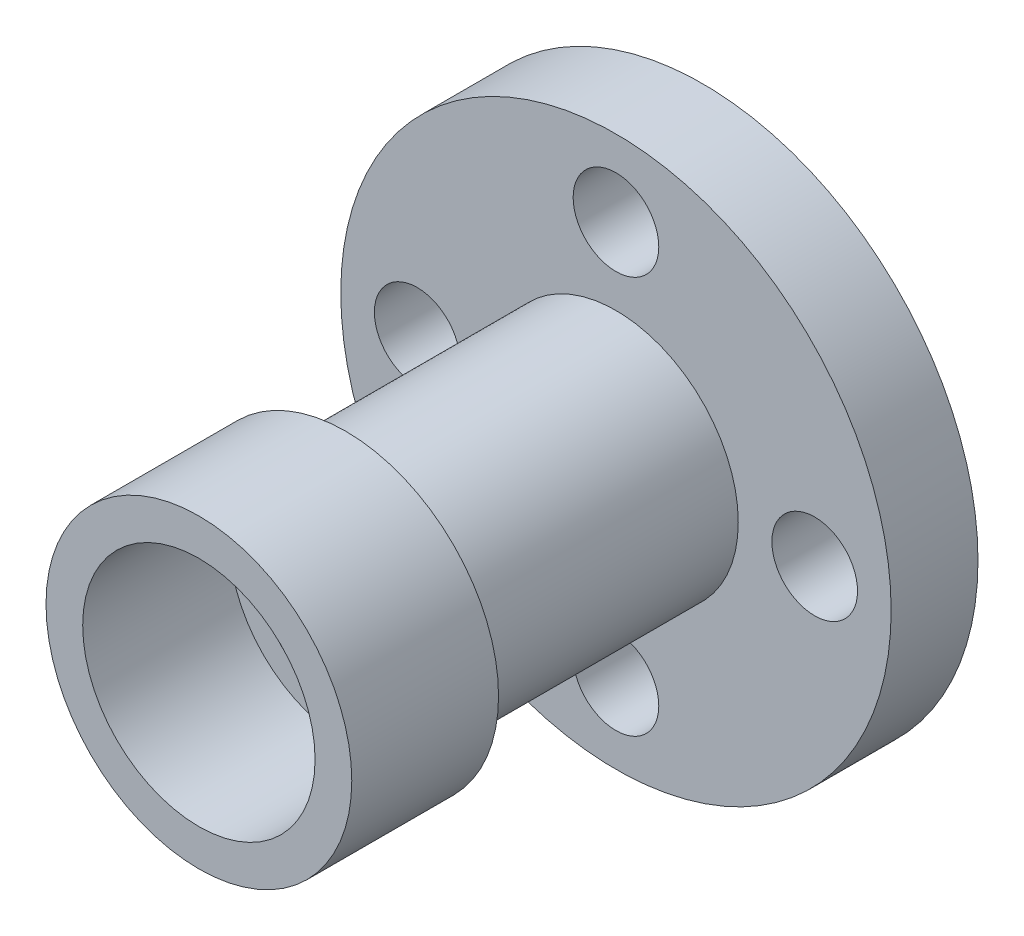
SolidWorks part; units mm, degrees
ref_plane "Alzado" through (0, 0, 0) normal (0, 0, 1) x (1, 0, 0)
ref_plane "Planta" through (0, 0, 0) normal (0, 1, 0) x (1, 0, 0)
ref_plane "Vista lateral" through (0, 0, 0) normal (1, 0, 0) x (0, 0, -1)
sketch "Croquis1" plane through (0, 0, 0) normal (0, 0, 1) x (1, 0, 0)
  circle A1 centre (0, 0) radius 45
extrude "Saliente-Extruir1" add sketch "Croquis1" along normal blind 14.2
sketch "Croquis6" plane through (0, 0, 14.2) normal (0, 0, 1) x (1, 0, 0)
  circle A0 centre (0, 0) radius 15
sketch "Croquis7" plane through (0, 0, 0) normal (0, 0, -1) x (-1, 0, 0)
  line L0 (0, 0) -> (0, 32.5) construction
  circle A0 centre (0, 0) radius 15
  circle A1 centre (0, 32.5) radius 7
  circle A2 centre (32.5, 0) radius 7
  circle A3 centre (0, -32.5) radius 7
  circle A4 centre (-32.5, 0) radius 7
  point P14 (0, 0)
  dimension "D2" = 4
  dimension "D1" = 32.5
sketch "Croquis8" plane through (0, 0, 14.2) normal (0, 0, 1) x (1, 0, 0)
  circle A0 centre (0, 0) radius 15
extrude "Saliente-Extruir13" add sketch "Croquis6" against normal blind 14 contours A0
extrude "Cortar-Extruir3" cut sketch "Croquis8" against normal blind 16 contours A0
sketch "Croquis2" plane through (0, 0, 0) normal (0, 0, 1) x (1, 0, 0)
  circle A0 centre (0, 0) radius 20
extrude "Saliente-Extruir3" add sketch "Croquis2" along normal blind 58.4 contours A0
sketch "Croquis5" plane through (0, 0, 58.4) normal (0, 0, 1) x (1, 0, 0)
  circle A0 centre (0, 0) radius 15
sketch "Croquis3" plane through (0, 0, 58.4) normal (0, 0, 1) x (1, 0, 0)
  circle A0 centre (0, 0) radius 25
  circle A1 centre (0, 0) radius 19
  dimension "D1" = 50
  dimension "D2" = 38
extrude "Saliente-Extruir4" add sketch "Croquis3" along normal blind 24 contours A0 | A1
sketch "Croquis4" plane through (0, 0, 82.4) normal (0, 0, 1) x (1, 0, 0)
  circle A0 centre (0, 0) radius 19
extrude "Cortar-Extruir4" cut sketch "Croquis5" against normal blind 59 contours A0
extrude "Cortar-Extruir18" cut sketch "Croquis7" against normal blind 17 contours A4 | A3 | A2 | A1
chamfer "Chaflán1" distance 3.5 distance2 3 1 edges at (15, 0, 0)
